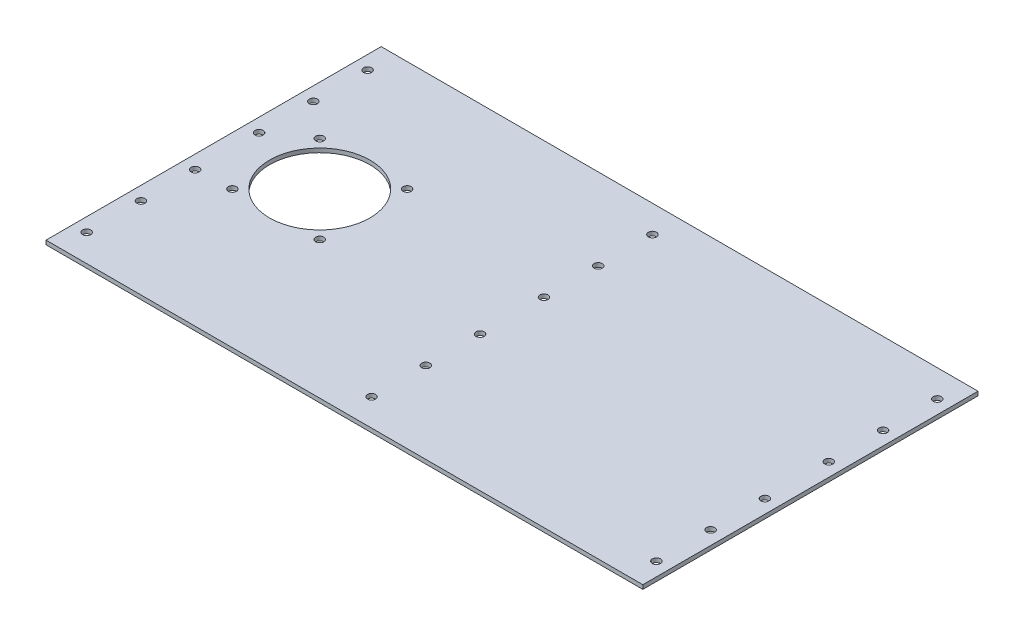
SolidWorks part; units mm, degrees
ref_plane "前视基准面" through (0, 0, 0) normal (0, 0, 1) x (1, 0, 0)
ref_plane "上视基准面" through (0, 0, 0) normal (0, 1, 0) x (1, 0, 0)
ref_plane "右视基准面" through (0, 0, 0) normal (1, 0, 0) x (0, 0, -1)
sketch "草图1" plane through (0, 0, 0) normal (0, 1, 0) x (1, 0, 0)
  line L1 (-65.705, 44.3173) -> (154.295, 44.3173)
  line L2 (-65.705, 44.3173) -> (-65.705, -79.2327)
  line L3 (-65.705, -79.2327) -> (154.295, -79.2327)
  line L4 (154.295, 44.3173) -> (154.295, -79.2327)
  dimension "D1" = 123.55
  dimension "D2" = 220
extrude "凸台-拉伸1" add sketch "草图1" along normal blind 1.5
sketch "草图2" plane through (0, 1.5, 0) normal (0, 1, 0) x (1, 0, 0)
  line L0 (-65.705, -17.4577) -> (-10.705, -17.4577)
  line L1 (154.295, -79.2327) -> (154.295, 44.3173) construction
  line L2 (-65.705, -17.4577) -> (154.295, -17.4577)
  line L3 (-65.705, 44.3173) -> (-65.705, -79.2327) construction
  line L4 (-38.205, -17.4577) -> (-22.105, -17.4577)
  line L5 (-65.705, -79.2327) -> (154.295, -79.2327) construction
  line L10 (-65.705, -17.4577) -> (-14.705, -17.4577)
  line L11 (-38.205, -17.4577) -> (-31.5703, -17.4577)
  line L12 (-31.5703, -17.4577) -> (-43.1134, -17.4577)
  line L13 (-31.5703, -17.4577) -> (-47.6703, -17.4577)
  line L14 (-47.6703, -33.5577) -> (-47.6703, -1.3577)
  line L15 (-47.6703, -1.3577) -> (-47.6703, 3.6423)
  line L16 (-65.705, -12.4577) -> (-10.705, -12.4577)
  line L17 (-31.5703, -17.4577) -> (-31.5703, -12.4577)
  circle A0 centre (149.295, -69.2327) radius 1.5
  circle A1 centre (44.295, -69.2327) radius 1.5
  circle A2 centre (-60.705, -69.2327) radius 1.5
  circle A3 centre (44.295, -49.2327) radius 1.5
  circle A4 centre (-60.705, -49.2327) radius 1.5
  circle A5 centre (149.295, -49.2327) radius 1.5
  circle A6 centre (149.295, 14.3173) radius 1.5
  circle A7 centre (-60.705, 14.3173) radius 1.5
  circle A8 centre (44.295, 14.3173) radius 1.5
  circle A9 centre (-60.705, 34.3173) radius 1.5
  circle A10 centre (44.295, 34.3173) radius 1.5
  circle A11 centre (149.295, 34.3173) radius 1.5
  circle A12 centre (149.295, -29.2327) radius 1.5
  circle A13 centre (44.295, -29.2327) radius 1.5
  circle A14 centre (-60.705, -29.2327) radius 1.5
  circle A15 centre (149.295, -5.6827) radius 1.5
  circle A16 centre (44.295, -5.6827) radius 1.5
  circle A17 centre (-60.705, -5.6827) radius 1.5
  circle A32 centre (-31.5703, -12.4577) radius 18.5
  circle A33 centre (-47.6703, 3.6423) radius 1.5
  circle A34 centre (-15.4703, 3.6423) radius 1.5
  circle A35 centre (-15.4703, -28.5577) radius 1.5
  circle A36 centre (-47.6703, -28.5577) radius 1.5
  point P51 (-22.105, -17.4577)
  point P52 (-47.6703, -17.4577)
  point P67 (-43.1134, -17.4577)
  dimension "D2" = 5
  dimension "D3" = 3
  dimension "D6" = 55
  dimension "D1" = 10
  dimension "D10" = 2
  dimension "D9" = 5
  dimension "D4" = 3
  dimension "D5" = 3
  dimension "D11" = 2
extrude "切除-拉伸1" cut sketch "草图2" against normal blind 10
